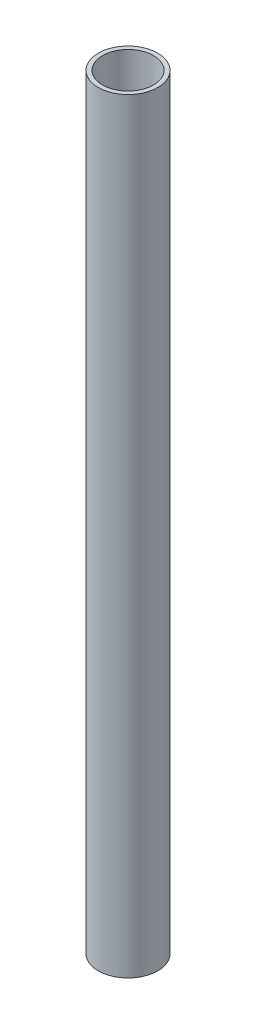
SolidWorks part; units mm, degrees
ref_plane "Front Plane" through (0, 0, 0) normal (0, 0, 1) x (1, 0, 0)
ref_plane "Top Plane" through (0, 0, 0) normal (0, 1, 0) x (1, 0, 0)
ref_plane "Right Plane" through (0, 0, 0) normal (1, 0, 0) x (0, 0, -1)
sketch "Sketch1" plane through (0, 0, 0) normal (0, 1, 0) x (1, 0, 0)
  circle A0 centre (0, 0) radius 9
extrude "Extrude-Thin1" add sketch "Sketch1" along normal blind 270 thin
